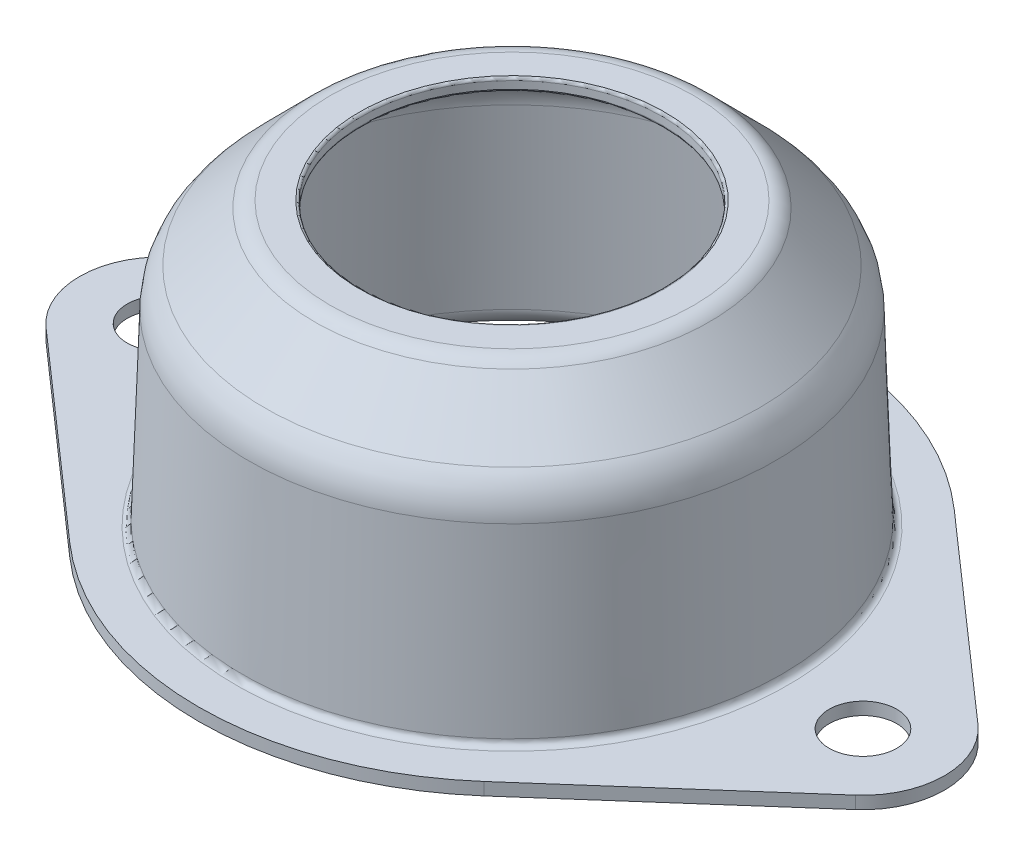
SolidWorks part; units mm, degrees
material "Plain Carbon Steel"
ref_plane "Front" through (0, 0, 0) normal (0, 0, 1) x (1, 0, 0)
ref_plane "Top" through (0, 0, 0) normal (0, 1, 0) x (1, 0, 0)
ref_plane "Right" through (0, 0, 0) normal (1, 0, 0) x (0, 0, -1)
sketch "Sketch2" plane through (0, 0, 0) normal (0, 1, 0) x (1, 0, 0)
  line L0 (-28, 0) -> (28, 0) construction
  line L1 (-16.5179, 18.7659) -> (-32.2946, 4.8791)
  line L2 (-28, 0) -> (-34.5, 0) construction
  line L3 (-32.2946, -4.8791) -> (-16.5179, -18.7659)
  line L4 (30.7, 0) -> (34.5, 0) construction
  line L5 (16.5179, -18.7659) -> (32.2946, -4.8791)
  line L7 (32.2946, 4.8791) -> (16.5179, 18.7659)
  circle A0 centre (-28, 0) radius 2.7
  circle A1 centre (28, 0) radius 2.7
  arc A2 (-16.5179, -18.7659) -> (16.5179, -18.7659) centre (0, 0) ccw
  arc A3 (16.5179, 18.7659) -> (-16.5179, 18.7659) centre (0, 0) ccw
  arc A4 (32.2946, 4.8791) -> (32.2946, -4.8791) centre (28, 0) cw
  arc A5 (-32.2946, 4.8791) -> (-32.2946, -4.8791) centre (-28, 0) ccw
  dimension "D1" = 56
  dimension "Flange Wd" = 50
  dimension "Bolt Hole Dia" = 5.4
  dimension "Flange Lg" = 69
  dimension "D2" = 3.8
extrude "BASE" add sketch "Sketch2" along normal blind 1
sketch "Sketch1" plane through (0, 0, 0) normal (0, 0, 1) x (1, 0, 0)
  line L0 (21, 16) -> (21.5, 1.5)
  line L1 (22, 1) -> (-22, 1) construction
  line L2 (14.5, 23.5) -> (0, 23.5)
  line L3 (0, 23.5) -> (0, 1)
  line L4 (0, 1) -> (22, 1)
  line L6 (19.7025, 19) -> (15.75, 22.9797)
  line L7 (16.5179, 1) -> (-16.5179, 1) construction
  line L8 (22, 1) -> (22, 1.5) construction
  line L9 (22, 1.5) -> (21.5, 1.5) construction
  line L10 (-21.5, 1.5) -> (21.5, 1.5) construction
  line L12 (-21, 16) -> (21, 16) construction
  line L13 (-19.7025, 19) -> (19.7025, 19) construction
  arc A2 (21.5, 1.5) -> (22, 1) centre (22, 1.5) ccw
  arc A3 (19.7025, 19) -> (21, 16) centre (16.5265, 15.8457) cw
  arc A4 (15.75, 22.9797) -> (14.5, 23.5) centre (14.5, 21.7383) ccw
  point P2 (0, 1.5)
  point P11 (0, 12.25)
  point P17 (0, 16)
  point P19 (0, 19)
  dimension "D5" = 43
  dimension "D6" = 15
  dimension "D1" = 22.5
  dimension "D3" = 0.5
  dimension "D4" = 44
  dimension "D2" = 1
  dimension "D8" = 14.5
  dimension "D10" = 42
  dimension "D11" = 1.7617
  dimension "D12" = 4.4762
  dimension "D7" = 18
  dimension "D9" = 15.75
revolve "TOP BODY" add sketch "Sketch1" angle 360 mid plane about L3
hole_wizard "M5 Clearance Hole2" positions "Sketch6" profile "Sketch5" hole size "M5" standard "ANSI Metric" end condition through all
sketch "Sketch6" plane through (0, 1, 0) normal (0, 1, 0) x (1, 0, 0)
  point P0 (-28, 0)
  point P3 (28, 0)
sketch "Sketch5" plane through (-28, 1, 0) normal (1, 0, 0) x (0, 0, 1)
  line L0 (0, 0) -> (0, 1)
  line L1 (0, 1) -> (2.7, 1)
  line L2 (2.7, 1) -> (2.7, 0)
  line L5 (2.7, 0) -> (0, 0)
  line L11 (0, -6.35) -> (0, 107.95) construction
  dimension "Thru Hole Dia." = 5.4
  dimension "Thru Hole Depth" = 1
sketch "Sketch8" plane through (0, 0, 0) normal (0, 0, 1) x (1, 0, 0)
  line L0 (-21, 16) -> (-21.5, 1.5) construction
  line L1 (-15.75, 22.9797) -> (-19.7025, 19) construction
  line L2 (-21, 16) -> (-21.5, 1.5) construction
  line L3 (-15.75, 22.9797) -> (-19.7025, 19) construction
  line L4 (-15.0405, 22.275) -> (-18.9929, 18.2953)
  line L5 (-20.0006, 15.9655) -> (-20.5002, 1.4781)
  line L6 (-22, 0) -> (0, 0)
  line L7 (0, 0) -> (0, 23.5)
  line L9 (14.5, 23.5) -> (-14.5, 23.5) construction
  line L10 (0, 23.5) -> (-12, 23.5)
  line L11 (-12, 23.5) -> (-12, 22.5)
  line L12 (-12, 22.5) -> (-14.5, 22.5)
  arc A0 (-22, 1) -> (-21.5, 1.5) centre (-22, 1.5) ccw construction
  arc A1 (-19.7025, 19) -> (-21, 16) centre (-16.5265, 15.8457) ccw construction
  arc A2 (-14.5, 23.5) -> (-15.75, 22.9797) centre (-14.5, 21.7383) ccw construction
  arc A3 (-22, 1) -> (-21.5, 1.5) centre (-22, 1.5) ccw construction
  arc A4 (-19.7025, 19) -> (-21, 16) centre (-16.5265, 15.8457) ccw construction
  arc A5 (-14.5, 23.5) -> (-15.75, 22.9797) centre (-14.5, 21.7383) ccw construction
  arc A6 (-14.5, 22.5) -> (-15.0405, 22.275) centre (-14.5, 21.7383) ccw
  arc A7 (-18.9929, 18.2953) -> (-20.0006, 15.9655) centre (-16.5265, 15.8457) ccw
  arc A8 (-22, 0) -> (-20.5002, 1.4781) centre (-22, 1.5) ccw
  dimension "D2" = 12
  dimension "D1" = 1
revolve "INNER BODY CUT" cut sketch "Sketch8" angle 360 about L7
fillet "IBC TOP F" radius 0.2 2 edges at (0, 23.5, -12) (0, 22.5, -12)
